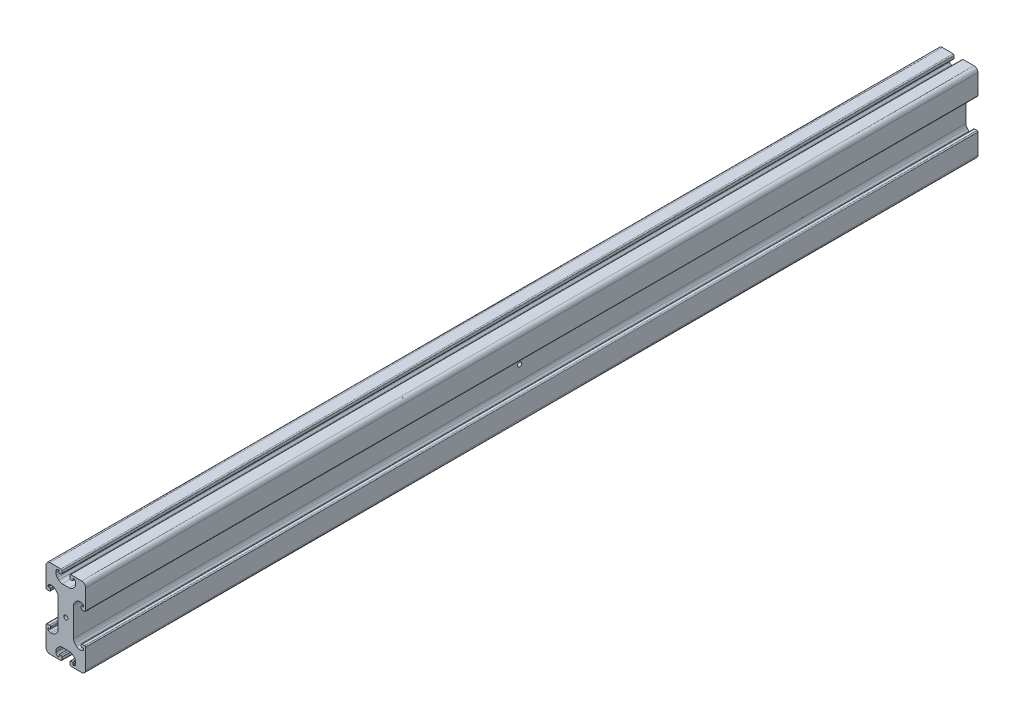
SolidWorks part; units mm, degrees
material "氧化铝"
ref_plane "前视基准面" through (0, 0, 0) normal (0, 0, 1) x (1, 0, 0)
ref_plane "上视基准面" through (0, 0, 0) normal (0, 1, 0) x (1, 0, 0)
ref_plane "右视基准面" through (0, 0, 0) normal (1, 0, 0) x (0, 0, -1)
sketch "Model" plane through (0, 0, 0) normal (0, 0, 1) x (1, 0, 0)
  line L64 (3046.1837, 1527.3048) -> (3046.1837, 1529.8049)
  line L65 (3052.8411, 1546.8271) -> (3051.3986, 1548.2695)
  line L66 (3057.6841, 1545.3625) -> (3056.3766, 1545.3625)
  line L67 (3058.1843, 1548.3625) -> (3059.7342, 1548.3625)
  line L68 (3060.1841, 1547.9126) -> (3060.1841, 1547.8625)
  line L69 (3057.6841, 1550.3626) -> (3057.6841, 1548.8625)
  line L70 (3061.1841, 1551.3625) -> (3058.6842, 1551.3625)
  line L71 (3038.626, 1538.5549) -> (3045.7412, 1538.5549)
  line L72 (3062.1837, 1530.305) -> (3062.1842, 1550.3626)
  line L73 (3049.1837, 1528.7549) -> (3049.1837, 1530.3049)
  line L74 (3047.1836, 1530.8048) -> (3048.6837, 1530.8048)
  line L75 (3049.6336, 1528.3048) -> (3049.6837, 1528.3048)
  line L76 (3050.7191, 1535.6478) -> (3049.2769, 1537.0902)
  line L77 (3052.1837, 1530.8048) -> (3052.1837, 1532.1123)
  line L78 (3047.1836, 1526.3048) -> (3058.1838, 1526.3047)
  line L79 (3037.1836, 1526.3048) -> (3026.1835, 1526.3047)
  line L80 (3032.1835, 1530.8048) -> (3032.1835, 1532.1123)
  line L81 (3033.6481, 1535.6478) -> (3035.0903, 1537.0902)
  line L82 (3034.7336, 1528.3048) -> (3034.6836, 1528.3048)
  line L83 (3037.1836, 1530.8048) -> (3035.6835, 1530.8048)
  line L84 (3035.1835, 1528.7549) -> (3035.1835, 1530.3049)
  line L85 (3022.1835, 1530.305) -> (3022.1836, 1550.3626)
  line L86 (3023.1838, 1551.3625) -> (3025.6836, 1551.3625)
  line L87 (3026.6838, 1550.3626) -> (3026.6838, 1548.8625)
  line L88 (3024.1837, 1547.9126) -> (3024.1837, 1547.8625)
  line L89 (3026.1836, 1548.3625) -> (3024.6336, 1548.3625)
  line L90 (3026.6838, 1545.3625) -> (3027.9912, 1545.3625)
  line L91 (3031.5268, 1546.8271) -> (3032.9692, 1548.2695)
  line L92 (3038.1835, 1527.3048) -> (3038.1835, 1529.8049)
  line L110 (3034.4339, 1580.805) -> (3034.4336, 1551.805)
  line L111 (3049.9343, 1580.805) -> (3049.9343, 1551.805)
  line L122 (3038.1844, 1605.3051) -> (3038.1843, 1602.8051)
  line L123 (3031.5272, 1585.783) -> (3032.9696, 1584.3406)
  line L124 (3026.6842, 1587.2477) -> (3027.9917, 1587.2477)
  line L125 (3026.1839, 1584.2477) -> (3024.634, 1584.2478)
  line L126 (3024.1841, 1584.6977) -> (3024.1841, 1584.7477)
  line L127 (3026.6841, 1582.2476) -> (3026.6841, 1583.7477)
  line L128 (3023.1841, 1581.2478) -> (3025.6839, 1581.2477)
  line L129 (3022.1843, 1602.3053) -> (3022.1839, 1582.2477)
  line L130 (3035.1843, 1603.8551) -> (3035.1843, 1602.3052)
  line L131 (3037.1844, 1601.8052) -> (3035.6842, 1601.8052)
  line L132 (3034.7344, 1604.3053) -> (3034.6844, 1604.3053)
  line L133 (3033.6488, 1596.9622) -> (3035.0909, 1595.5198)
  line L134 (3032.1843, 1601.8053) -> (3032.1842, 1600.4978)
  line L135 (3037.1845, 1606.3052) -> (3026.1843, 1606.3055)
  line L136 (3047.1845, 1606.305) -> (3058.1846, 1606.3049)
  line L137 (3052.1845, 1601.8048) -> (3052.1845, 1600.4973)
  line L138 (3050.7198, 1596.9619) -> (3049.2775, 1595.5195)
  line L139 (3049.6344, 1604.3049) -> (3049.6845, 1604.3049)
  line L140 (3047.1844, 1601.8049) -> (3048.6845, 1601.8049)
  line L141 (3049.1845, 1603.8548) -> (3049.1845, 1602.3049)
  line L142 (3062.1845, 1602.3045) -> (3062.1842, 1582.2472)
  line L143 (3038.6266, 1594.0551) -> (3045.7418, 1594.0549)
  line L144 (3061.1841, 1581.2473) -> (3058.6842, 1581.2473)
  line L145 (3057.6841, 1582.2473) -> (3057.6841, 1583.7474)
  line L146 (3060.1842, 1584.6972) -> (3060.1842, 1584.7473)
  line L147 (3058.1843, 1584.2474) -> (3059.7343, 1584.2473)
  line L148 (3057.6842, 1587.2474) -> (3056.3767, 1587.2474)
  line L149 (3052.8412, 1585.7829) -> (3051.3987, 1584.3405)
  line L150 (3046.1845, 1605.3049) -> (3046.1845, 1602.8049)
  spline S0 degree 3 poles (3047.1836, 1526.3048) (3046.9672, 1526.3048) (3046.4685, 1526.5226) (3046.1837, 1526.9491) (3046.1837, 1527.3048) knots 0 0 0 0 0.421034 1 1 1 1
  spline S1 degree 3 poles (3051.3986, 1548.2695) (3050.9343, 1548.7338) (3050.2403, 1549.8258) (3049.9343, 1551.1085) (3049.9343, 1551.805) knots 0 0 0 0 0.481772 1 1 1 1
  spline S2 degree 3 poles (3056.3766, 1545.3625) (3055.6979, 1545.3625) (3054.43, 1545.6352) (3053.3248, 1546.3434) (3052.8411, 1546.8271) knots 0 0 0 0 0.495307 1 1 1 1
  spline S3 degree 3 poles (3060.1841, 1547.8625) (3060.1841, 1547.0307) (3059.5342, 1545.9346) (3058.2861, 1545.3625) (3057.6841, 1545.3625) knots 0 0 0 0 0.543506 1 1 1 1
  spline S4 degree 3 poles (3059.7342, 1548.3625) (3059.9011, 1548.3625) (3060.09, 1548.2279) (3060.1841, 1548.0038) (3060.1841, 1547.9126) knots 0 0 0 0 0.601272 1 1 1 1
  spline S5 degree 3 poles (3057.6841, 1548.8625) (3057.6841, 1548.6963) (3057.8141, 1548.4771) (3058.0638, 1548.3625) (3058.1843, 1548.3625) knots 0 0 0 0 0.543008 1 1 1 1
  spline S6 degree 3 poles (3058.6842, 1551.3625) (3058.3483, 1551.3625) (3057.9116, 1551.099) (3057.6841, 1550.5998) (3057.6841, 1550.3626) knots 0 0 0 0 0.548464 1 1 1 1
  spline S7 degree 3 poles (3062.1842, 1550.3626) (3062.1842, 1550.6998) (3061.9191, 1551.1358) (3061.4198, 1551.3625) (3061.1841, 1551.3625) knots 0 0 0 0 0.550415 1 1 1 1
  spline S8 degree 3 poles (3049.6837, 1528.3048) (3050.3809, 1528.3048) (3051.6238, 1528.9085) (3052.1837, 1530.0457) (3052.1837, 1530.8048) knots 0 0 0 0 0.502794 1 1 1 1
  spline S9 degree 3 poles (3049.1837, 1528.7549) (3049.1837, 1528.6211) (3049.3106, 1528.3999) (3049.5141, 1528.3048) (3049.6336, 1528.3048) knots 0 0 0 0 0.549542 1 1 1 1
  spline S10 degree 3 poles (3048.6837, 1530.8048) (3048.8146, 1530.8048) (3049.0639, 1530.6873) (3049.1837, 1530.4632) (3049.1837, 1530.3049) knots 0 0 0 0 0.482406 1 1 1 1
  spline S11 degree 3 poles (3046.1837, 1529.8049) (3046.1837, 1530.1088) (3046.4776, 1530.5989) (3046.9298, 1530.8048) (3047.1836, 1530.8048) knots 0 0 0 0 0.565195 1 1 1 1
  spline S12 degree 3 poles (3049.2769, 1537.0902) (3048.8108, 1537.5565) (3047.7046, 1538.2661) (3046.4411, 1538.5549) (3045.7412, 1538.5549) knots 0 0 0 0 0.489373 1 1 1 1
  spline S13 degree 3 poles (3052.1837, 1532.1123) (3052.1837, 1532.8016) (3051.8923, 1534.0839) (3051.1926, 1535.1743) (3050.7191, 1535.6478) knots 0 0 0 0 0.510204 1 1 1 1
  spline S14 degree 3 poles (3058.1838, 1526.3047) (3059.5327, 1526.3047) (3061.2765, 1527.3653) (3062.1837, 1529.3623) (3062.1837, 1530.305) knots 0 0 0 0 0.550548 1 1 1 1
  spline S45 degree 3 poles (3026.1835, 1526.3047) (3024.8345, 1526.3047) (3023.0907, 1527.3653) (3022.1835, 1529.3623) (3022.1835, 1530.305) knots 0 0 0 0 0.550548 1 1 1 1
  spline S46 degree 3 poles (3032.1835, 1532.1123) (3032.1835, 1532.8016) (3032.4749, 1534.0839) (3033.1746, 1535.1743) (3033.6481, 1535.6478) knots 0 0 0 0 0.510204 1 1 1 1
  spline S47 degree 3 poles (3035.0903, 1537.0902) (3035.5565, 1537.5565) (3036.6626, 1538.2661) (3037.9261, 1538.5549) (3038.626, 1538.5549) knots 0 0 0 0 0.489373 1 1 1 1
  spline S48 degree 3 poles (3038.1835, 1529.8049) (3038.1835, 1530.1088) (3037.8896, 1530.5989) (3037.4374, 1530.8048) (3037.1836, 1530.8048) knots 0 0 0 0 0.565195 1 1 1 1
  spline S49 degree 3 poles (3035.6835, 1530.8048) (3035.5526, 1530.8048) (3035.3033, 1530.6873) (3035.1835, 1530.4632) (3035.1835, 1530.3049) knots 0 0 0 0 0.482406 1 1 1 1
  spline S50 degree 3 poles (3035.1835, 1528.7549) (3035.1835, 1528.6211) (3035.0566, 1528.3999) (3034.8531, 1528.3048) (3034.7336, 1528.3048) knots 0 0 0 0 0.549542 1 1 1 1
  spline S51 degree 3 poles (3034.6836, 1528.3048) (3033.9863, 1528.3048) (3032.7434, 1528.9085) (3032.1835, 1530.0457) (3032.1835, 1530.8048) knots 0 0 0 0 0.502794 1 1 1 1
  spline S52 degree 3 poles (3022.1836, 1550.3626) (3022.1836, 1550.6998) (3022.4487, 1551.1358) (3022.948, 1551.3625) (3023.1838, 1551.3625) knots 0 0 0 0 0.550415 1 1 1 1
  spline S53 degree 3 poles (3025.6836, 1551.3625) (3026.0195, 1551.3625) (3026.4562, 1551.099) (3026.6838, 1550.5998) (3026.6838, 1550.3626) knots 0 0 0 0 0.548464 1 1 1 1
  spline S54 degree 3 poles (3026.6838, 1548.8625) (3026.6838, 1548.6963) (3026.5537, 1548.4771) (3026.304, 1548.3625) (3026.1836, 1548.3625) knots 0 0 0 0 0.543008 1 1 1 1
  spline S55 degree 3 poles (3024.6336, 1548.3625) (3024.4667, 1548.3625) (3024.2779, 1548.2279) (3024.1837, 1548.0038) (3024.1837, 1547.9126) knots 0 0 0 0 0.601272 1 1 1 1
  spline S56 degree 3 poles (3024.1837, 1547.8625) (3024.1837, 1547.0307) (3024.8336, 1545.9346) (3026.0818, 1545.3625) (3026.6838, 1545.3625) knots 0 0 0 0 0.543506 1 1 1 1
  spline S57 degree 3 poles (3027.9912, 1545.3625) (3028.6699, 1545.3625) (3029.9378, 1545.6352) (3031.043, 1546.3434) (3031.5268, 1546.8271) knots 0 0 0 0 0.495307 1 1 1 1
  spline S58 degree 3 poles (3032.9692, 1548.2695) (3033.4335, 1548.7338) (3034.1275, 1549.8258) (3034.4336, 1551.1085) (3034.4336, 1551.805) knots 0 0 0 0 0.481772 1 1 1 1
  spline S59 degree 3 poles (3037.1836, 1526.3048) (3037.4, 1526.3048) (3037.8988, 1526.5226) (3038.1835, 1526.9491) (3038.1835, 1527.3048) knots 0 0 0 0 0.421034 1 1 1 1
  spline S64 degree 3 poles (3037.1845, 1606.3052) (3037.4009, 1606.3052) (3037.8996, 1606.0874) (3038.1844, 1605.6609) (3038.1844, 1605.3051) knots 0 0 0 0 0.421034 1 1 1 1
  spline S65 degree 3 poles (3032.9696, 1584.3406) (3033.4339, 1583.8762) (3034.1278, 1582.7842) (3034.4339, 1581.5016) (3034.4339, 1580.805) knots 0 0 0 0 0.481772 1 1 1 1
  spline S66 degree 3 poles (3027.9917, 1587.2477) (3028.6703, 1587.2477) (3029.9382, 1586.9749) (3031.0435, 1586.2668) (3031.5272, 1585.783) knots 0 0 0 0 0.495307 1 1 1 1
  spline S67 degree 3 poles (3024.1841, 1584.7477) (3024.1841, 1585.5796) (3024.834, 1586.6756) (3026.0822, 1587.2477) (3026.6842, 1587.2477) knots 0 0 0 0 0.543506 1 1 1 1
  spline S68 degree 3 poles (3024.634, 1584.2478) (3024.4671, 1584.2478) (3024.2783, 1584.3823) (3024.1841, 1584.6065) (3024.1841, 1584.6977) knots 0 0 0 0 0.601272 1 1 1 1
  spline S69 degree 3 poles (3026.6841, 1583.7477) (3026.6841, 1583.9139) (3026.5541, 1584.1331) (3026.3044, 1584.2477) (3026.1839, 1584.2477) knots 0 0 0 0 0.543008 1 1 1 1
  spline S70 degree 3 poles (3025.6839, 1581.2477) (3026.0198, 1581.2477) (3026.4565, 1581.5112) (3026.6841, 1582.0104) (3026.6841, 1582.2476) knots 0 0 0 0 0.548464 1 1 1 1
  spline S71 degree 3 poles (3022.1839, 1582.2477) (3022.1839, 1581.9105) (3022.449, 1581.4745) (3022.9483, 1581.2478) (3023.1841, 1581.2478) knots 0 0 0 0 0.550415 1 1 1 1
  spline S72 degree 3 poles (3034.6844, 1604.3053) (3033.9871, 1604.3053) (3032.7442, 1603.7015) (3032.1843, 1602.5644) (3032.1843, 1601.8053) knots 0 0 0 0 0.502794 1 1 1 1
  spline S73 degree 3 poles (3035.1843, 1603.8551) (3035.1843, 1603.9889) (3035.0574, 1604.2101) (3034.8539, 1604.3053) (3034.7344, 1604.3053) knots 0 0 0 0 0.549542 1 1 1 1
  spline S74 degree 3 poles (3035.6842, 1601.8052) (3035.5534, 1601.8052) (3035.304, 1601.9227) (3035.1843, 1602.1468) (3035.1843, 1602.3052) knots 0 0 0 0 0.482406 1 1 1 1
  spline S75 degree 3 poles (3038.1843, 1602.8051) (3038.1843, 1602.5012) (3037.8904, 1602.0111) (3037.4381, 1601.8051) (3037.1844, 1601.8052) knots 0 0 0 0 0.565195 1 1 1 1
  spline S76 degree 3 poles (3035.0909, 1595.5198) (3035.5571, 1595.0535) (3036.6632, 1594.3439) (3037.9267, 1594.0551) (3038.6266, 1594.0551) knots 0 0 0 0 0.489373 1 1 1 1
  spline S77 degree 3 poles (3032.1842, 1600.4978) (3032.1842, 1599.8085) (3032.4756, 1598.5262) (3033.1753, 1597.4358) (3033.6488, 1596.9622) knots 0 0 0 0 0.510204 1 1 1 1
  spline S78 degree 3 poles (3026.1843, 1606.3055) (3024.8354, 1606.3056) (3023.0916, 1605.245) (3022.1843, 1603.2479) (3022.1843, 1602.3053) knots 0 0 0 0 0.550548 1 1 1 1
  spline S105 degree 3 poles (3058.1846, 1606.3049) (3059.5336, 1606.3048) (3061.2773, 1605.2441) (3062.1845, 1603.2471) (3062.1845, 1602.3045) knots 0 0 0 0 0.550548 1 1 1 1
  spline S106 degree 3 poles (3052.1845, 1600.4973) (3052.1844, 1599.8081) (3051.893, 1598.5258) (3051.1932, 1597.4354) (3050.7198, 1596.9619) knots 0 0 0 0 0.510204 1 1 1 1
  spline S107 degree 3 poles (3049.2775, 1595.5195) (3048.8114, 1595.0532) (3047.7052, 1594.3437) (3046.4417, 1594.0549) (3045.7418, 1594.0549) knots 0 0 0 0 0.489373 1 1 1 1
  spline S108 degree 3 poles (3046.1845, 1602.8049) (3046.1845, 1602.501) (3046.4784, 1602.0109) (3046.9306, 1601.8049) (3047.1844, 1601.8049) knots 0 0 0 0 0.565195 1 1 1 1
  spline S109 degree 3 poles (3048.6845, 1601.8049) (3048.8153, 1601.8049) (3049.0647, 1601.9224) (3049.1845, 1602.1465) (3049.1845, 1602.3049) knots 0 0 0 0 0.482406 1 1 1 1
  spline S110 degree 3 poles (3049.1845, 1603.8548) (3049.1845, 1603.9886) (3049.3114, 1604.2098) (3049.5149, 1604.3049) (3049.6344, 1604.3049) knots 0 0 0 0 0.549542 1 1 1 1
  spline S111 degree 3 poles (3049.6845, 1604.3049) (3050.3817, 1604.3049) (3051.6246, 1603.7011) (3052.1845, 1602.564) (3052.1845, 1601.8048) knots 0 0 0 0 0.502794 1 1 1 1
  spline S112 degree 3 poles (3062.1842, 1582.2472) (3062.1842, 1581.91) (3061.9192, 1581.474) (3061.4198, 1581.2473) (3061.1841, 1581.2473) knots 0 0 0 0 0.550415 1 1 1 1
  spline S113 degree 3 poles (3058.6842, 1581.2473) (3058.3483, 1581.2473) (3057.9116, 1581.5109) (3057.6841, 1582.0101) (3057.6841, 1582.2473) knots 0 0 0 0 0.548464 1 1 1 1
  spline S114 degree 3 poles (3057.6841, 1583.7474) (3057.6841, 1583.9136) (3057.8142, 1584.1327) (3058.0639, 1584.2474) (3058.1843, 1584.2474) knots 0 0 0 0 0.543008 1 1 1 1
  spline S115 degree 3 poles (3059.7343, 1584.2473) (3059.9012, 1584.2473) (3060.09, 1584.3819) (3060.1842, 1584.606) (3060.1842, 1584.6972) knots 0 0 0 0 0.601272 1 1 1 1
  spline S116 degree 3 poles (3060.1842, 1584.7473) (3060.1842, 1585.5791) (3059.5344, 1586.6752) (3058.2862, 1587.2474) (3057.6842, 1587.2474) knots 0 0 0 0 0.543506 1 1 1 1
  spline S117 degree 3 poles (3056.3767, 1587.2474) (3055.6981, 1587.2474) (3054.4302, 1586.9747) (3053.3249, 1586.2666) (3052.8412, 1585.7829) knots 0 0 0 0 0.495307 1 1 1 1
  spline S118 degree 3 poles (3051.3987, 1584.3405) (3050.9344, 1583.8762) (3050.2404, 1582.7842) (3049.9343, 1581.5016) (3049.9343, 1580.805) knots 0 0 0 0 0.481772 1 1 1 1
  spline S119 degree 3 poles (3047.1845, 1606.305) (3046.9681, 1606.305) (3046.4693, 1606.0872) (3046.1845, 1605.6607) (3046.1845, 1605.3049) knots 0 0 0 0 0.421034 1 1 1 1
  point P4 (3034.4337, 1566.305)
  point P53 (3034.4337, 1566.305)
  point P56 (3049.9343, 1566.305)
extrude "凸台-拉伸3" add sketch "Model" along normal blind 900 contours S1 L111 S118 L149 S117 L148 S116 L146 S115 L147 S114 L145 S113 L144 S112 L142 S105 L136 S119 L150 S108 L140 S109 L141 S110 L139 S111 L137 S106 L138 S107 L143 S76 L133 S77 L134 S72 L132 S73 L130 S74 L131 S75 L122 S64 L135 S78 L129 S71 L128 S70 L127 S69 L125 S68 L126 S67 L124 S66 L123 S65 L110 S58 L91 S57 L90 S56 L88 S55 L89 S54 L87 S53 L86 S52 L85 S45 L79 S59 L92 S48 L83 S49 L84 S50 L82 S51 L80 S46 L81 S47 L71 S12 L76 S13 L77 S8 L75 S9 L73 S10 L74 S11 L64 S0 L78 S14 L72 S7 L70 S6 L69 S5 L67 S4 L68 S3 L66 S2 L65
sketch "草图1" plane through (0, 0, 900) normal (0, 0, 1) x (1, 0, 0)
  point P0 (3042.1842, 1566.305)
hole_wizard "M5 螺纹孔1" positions "草图2" profile "草图3" tap size "M5" standard "GB" end condition through all
sketch "草图2" plane through (0, 0, 900) normal (0, 0, 1) x (1, 0, 0)
  point P0 (3042.1842, 1566.305)
sketch "草图3" plane through (3042.1842, 1566.305, 900) normal (1, 0, 0) x (0, -1, 0)
  line L0 (0, 0) -> (0, 900)
  line L1 (0, 900) -> (2.1, 900)
  line L2 (2.1, 900) -> (2.1, 0)
  line L5 (2.1, 0) -> (0, 0)
  line L11 (0, -6.35) -> (0, 107.95) construction
  dimension "通孔螺纹孔钻头直径" = 4.2
  dimension "通孔螺纹孔钻头深度" = 900
cosmetic thread "孔螺蚊线1" parameters "D2"=5
ref_plane "基准面2" through (3022.1843, 0, 0) normal (1, 0, 0) x (0, 0, -1)
ref_plane "基准面3" through (3062.1843, 0, 0) normal (1, 0, 0) x (0, 0, -1)
sketch "草图4" plane through (3034.4169, -0.0325, 0) normal (-1, 0, 0) x (0, 0, 1)
  line L0 (0, 1580.8375) -> (0, 1551.8375) construction
  point P0 (450, 1566.3375)
  dimension "D1" = 450
hole_wizard "M5 螺纹孔2" positions "草图5" profile "草图6" tap size "M5" standard "GB" end condition through all
sketch "草图5" plane through (3034.4169, -0.0325, 0) normal (-1, 0, 0) x (0, 0, 1)
  point P0 (450, 1566.3375)
sketch "草图6" plane through (3034.4337, 1566.305, 450) normal (0, 0, 1) x (0, -1, 0)
  line L0 (0, 0) -> (0, 27.7512)
  line L1 (0, 27.7512) -> (2.1, 27.7512)
  line L2 (2.1, 27.7512) -> (2.1, 0)
  line L5 (2.1, 0) -> (0, 0)
  line L11 (0, -6.35) -> (0, 107.95) construction
  dimension "通孔螺纹孔钻头直径" = 4.2
  dimension "通孔螺纹孔钻头深度" = 27.7512
cosmetic thread "孔螺蚊线2" parameters "D2"=5
